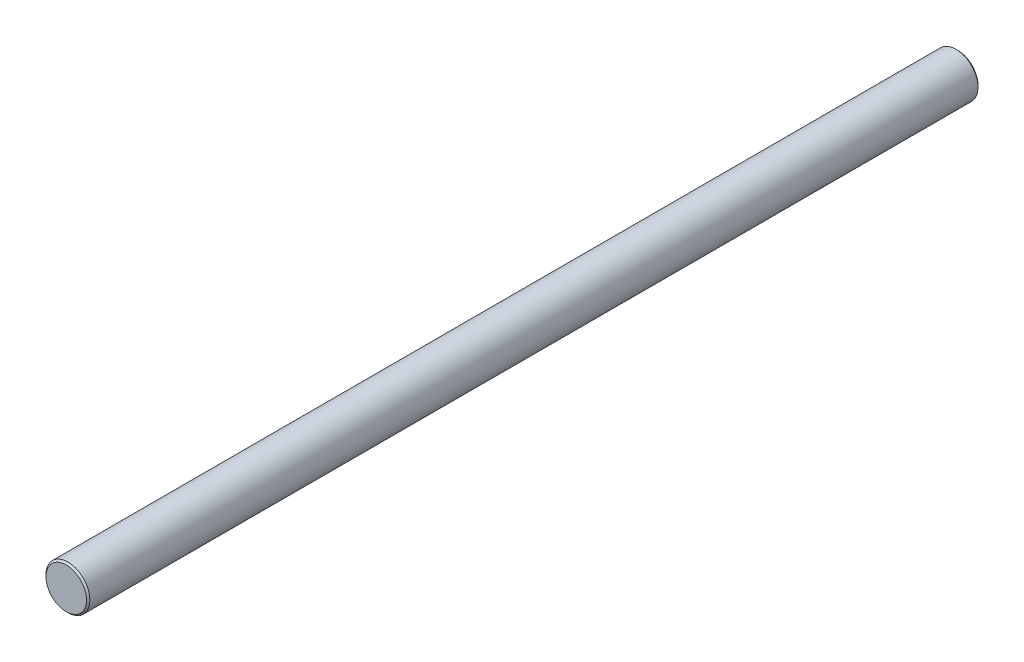
SolidWorks part; units mm, degrees
ref_plane "Front Plane" through (0, 0, 0) normal (0, 0, 1) x (1, 0, 0)
ref_plane "Top Plane" through (0, 0, 0) normal (0, 1, 0) x (1, 0, 0)
ref_plane "Right Plane" through (0, 0, 0) normal (1, 0, 0) x (0, 0, -1)
sketch "Sketch1" plane through (0, 0, 0) normal (0, 0, 1) x (1, 0, 0)
  circle A0 centre (0, 0) radius 10
  dimension "D1" = 20
extrude "Boss-Extrude1" add sketch "Sketch1" along normal mid plane 406.4
chamfer "Chamfer1" distance 0.762 angle 45 2 edges at (10, 0, -203.2) (10, 0, 203.2)
